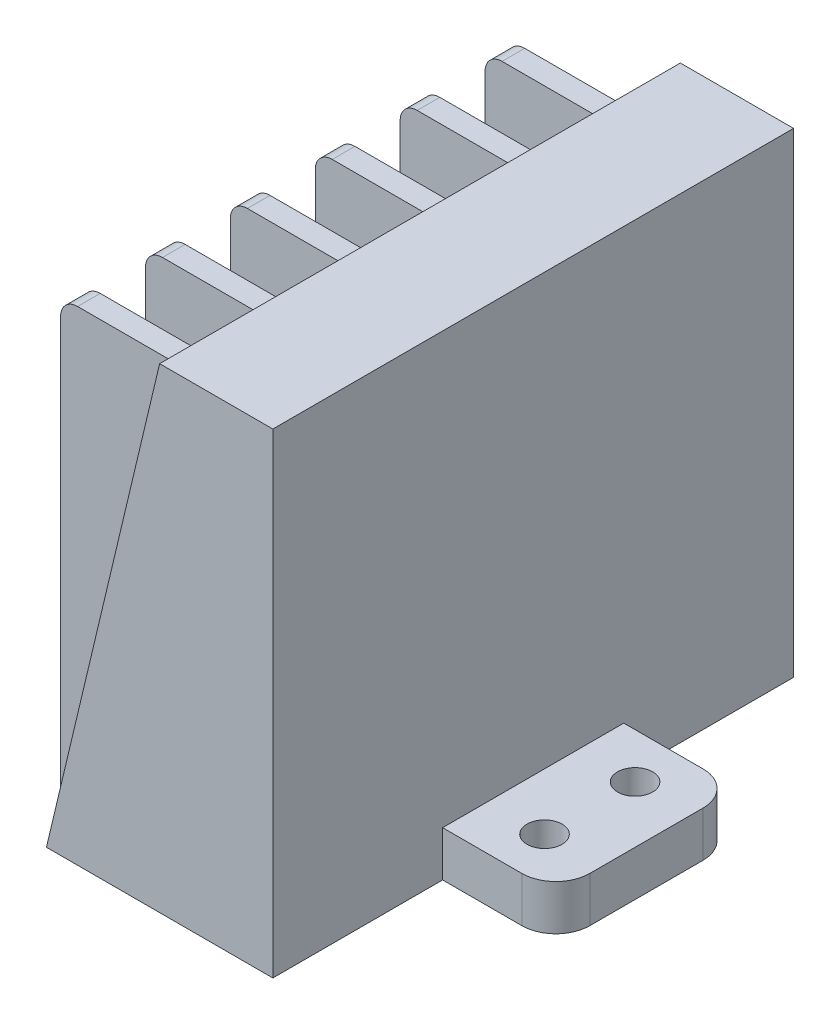
SolidWorks part; units mm, degrees
ref_plane "Front" through (0, 0, 0) normal (0, 0, 1) x (1, 0, 0)
ref_plane "Top" through (0, 0, 0) normal (0, 1, 0) x (1, 0, 0)
ref_plane "Right" through (0, 0, 0) normal (1, 0, 0) x (0, 0, -1)
sketch "Sketch1" plane through (0, 0, 0) normal (0, 0, 1) x (1, 0, 0)
  line L0 (0, 0) -> (0, 42)
  line L1 (0, 42) -> (-10, 42)
  line L2 (-10, 42) -> (-20, 0)
  line L3 (-20, 0) -> (0, 0)
  dimension "D1" = 42
  dimension "D2" = 10
  dimension "D3" = 20
extrude "Boss-Extrude1" add sketch "Sketch1" along normal blind 46
ref_plane "Plane1" through (0, 0, 42.75) normal (0, 0, 1) x (1, 0, 0)
sketch "Sketch2" plane through (0, 0, 42.75) normal (0, 0, 1) x (1, 0, 0)
  line L0 (-10.5952, 39.5) -> (-20.5, 39.5)
  line L1 (-10, 42) -> (-20, 0) construction
  line L2 (-20, 0) -> (-20.5, 0)
  line L3 (-22, 1.5) -> (-22, 38)
  line L4 (0, 42) -> (-10, 42) construction
  line L5 (-10.5952, 39.5) -> (-20, 0)
  arc A0 (-20.5, 39.5) -> (-22, 38) centre (-20.5, 38) ccw
  arc A1 (-22, 1.5) -> (-20.5, 0) centre (-20.5, 1.5) ccw
  dimension "D3" = 1.5
  dimension "D4" = 1.5
  dimension "D1" = 2.5
  dimension "D2" = 2
extrude "Boss-Extrude2" add sketch "Sketch2" against normal blind 2
pattern_linear "LPattern1" count 6 spacing 7.5 along (0, 0, -1) of "Boss-Extrude2"
ref_plane "Plane2" through (0, 0, 23) normal (0, 0, 1) x (1, 0, 0)
sketch "Sketch3" plane through (0, 0, 23) normal (0, 0, 1) x (1, 0, 0)
  line L8 (0, 0) -> (10, 0)
  line L9 (0, 0) -> (0, 4)
  line L10 (0, 4) -> (10, 4)
  line L11 (10, 0) -> (10, 4)
  line L12 (0, 0) -> (10, 4) construction
  line L13 (0, 4) -> (10, 0) construction
  point P4 (5, 2)
  dimension "D1" = 4
  dimension "D2" = 10
extrude "Boss-Extrude3" add sketch "Sketch3" along normal mid plane 16
sketch "Sketch4" plane through (0, 4, 0) normal (0, 1, 0) x (1, 0, 0)
  line L0 (10, -31) -> (10, -15) construction
  line L1 (10, -15) -> (0, -15) construction
  line L2 (10, -31) -> (0, -31) construction
  circle A0 centre (5, -19) radius 1.55
  circle A1 centre (5, -27) radius 1.55
  point P4 (0, 0)
  dimension "D1" = 3.1
  dimension "D2" = 3.1
  dimension "D3" = 5
  dimension "D4" = 4
  dimension "D5" = 4
extrude "Cut-Extrude1" cut sketch "Sketch4" against normal up to next
fillet "Fillet1" radius 3 2 edges at (10, 2, 15) (10, 2, 31)
